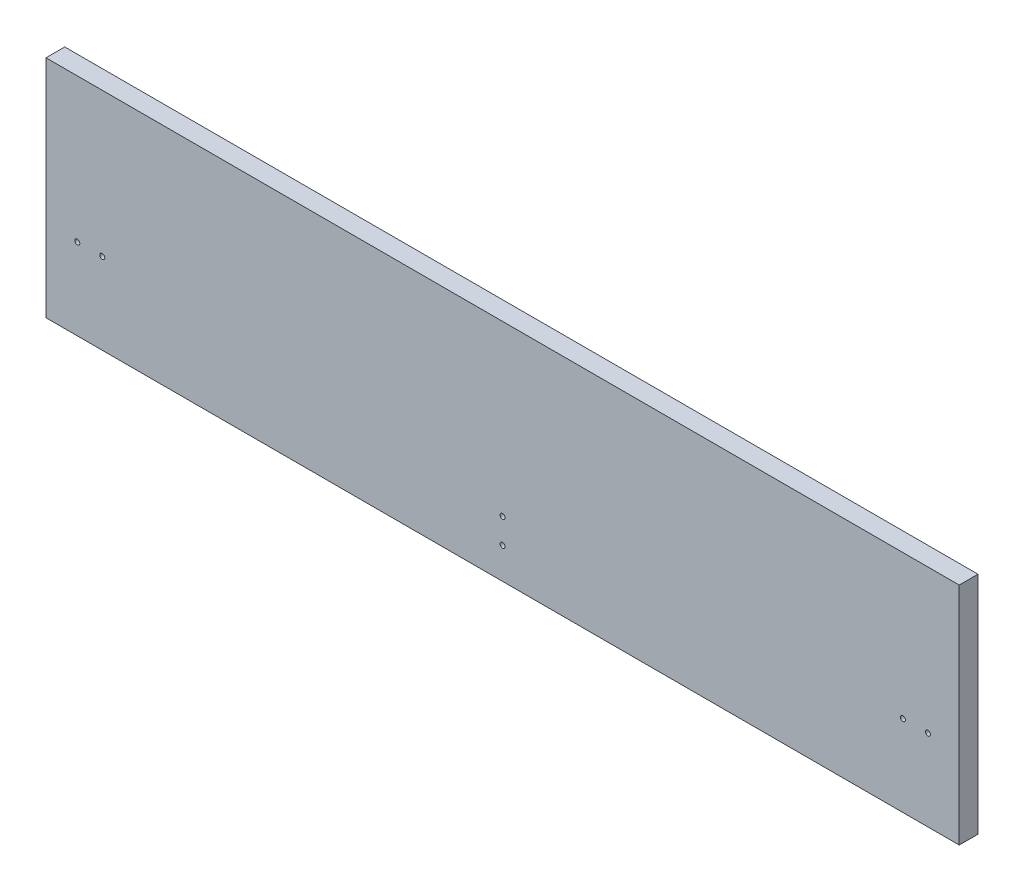
SolidWorks part; units mm, degrees
ref_plane "Alzado" through (0, 0, 0) normal (0, 0, 1) x (1, 0, 0)
ref_plane "Planta" through (0, 0, 0) normal (0, 1, 0) x (1, 0, 0)
ref_plane "Vista lateral" through (0, 0, 0) normal (1, 0, 0) x (0, 0, -1)
sketch "Croquis1" plane through (0, 0, 0) normal (0, 0, 1) x (1, 0, 0)
  line L1 (-365, -90) -> (365, -90)
  line L2 (-365, -90) -> (-365, 90)
  line L3 (-365, 90) -> (365, 90)
  line L4 (365, -90) -> (365, 90)
  line L5 (-365, -90) -> (365, 90) construction
  line L6 (-365, 90) -> (365, -90) construction
  point P0 (0, 0)
extrude "Saliente-Extruir1" add sketch "Croquis1" along normal blind 15
sketch "Croquis2" plane through (0, 0, 15) normal (0, 0, 1) x (1, 0, 0)
  line L0 (-365, -90) -> (365, -90) construction
  line L1 (-365, 90) -> (-365, -90) construction
  line L2 (365, -90) -> (365, 90) construction
  circle A0 centre (-340, -25) radius 2
  circle A1 centre (0, -65) radius 2
  circle A2 centre (0, -45) radius 2
  circle A3 centre (-320, -25) radius 2
  circle A4 centre (340, -25) radius 2
  circle A5 centre (320, -25) radius 2
  point P7 (0, -90)
  dimension "D1" = 25
  dimension "D3" = 25
  dimension "D7" = 25
  dimension "D2" = 20
  dimension "D4" = 20
  dimension "D5" = 65
  dimension "D6" = 0
  dimension "D8" = 20
  dimension "D9" = 65
extrude "Cortar-Extruir1" cut sketch "Croquis2" against normal blind 10
